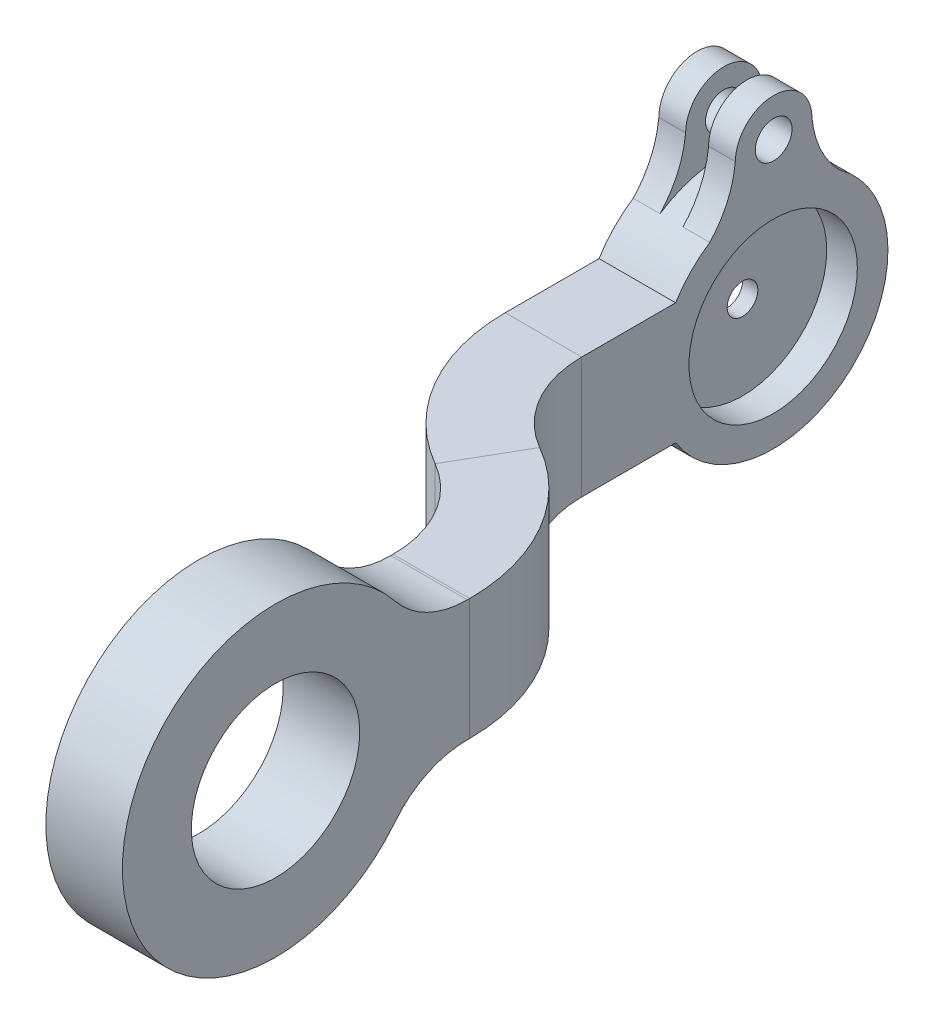
SolidWorks part; units mm, degrees
material "Resina de melamina"
ref_plane "Alzado" through (0, 0, 0) normal (0, 0, 1) x (1, 0, 0)
ref_plane "Planta" through (0, 0, 0) normal (0, 1, 0) x (1, 0, 0)
ref_plane "Vista lateral" through (0, 0, 0) normal (1, 0, 0) x (0, 0, -1)
sketch "Croquis1" plane through (0, 0, 0) normal (0, 1, 0) x (1, 0, 0)
  line L0 (0, 0) -> (0, 60) construction
  line L1 (0, 60) -> (-20, 60) construction
  line L2 (-20, 60) -> (-20, 85) construction
  line L3 (0, 15) -> (-20, 25.359) construction
  line L4 (-20, 85) -> (-20, 60)
  line L5 (0, 25.359) -> (0, 0)
  arc A0 (-20, 60) -> (-10, 42.6795) centre (0, 60) ccw
  arc A1 (0, 25.359) -> (-10, 42.6795) centre (-20, 25.359) ccw
  dimension "D4" = 20
  dimension "D1" = 60
  dimension "D2" = 25
  dimension "D3" = 20
sketch "Croquis2" plane through (0, 0, 0) normal (0, 0, 1) x (1, 0, 0)
  line L1 (5, -7.9175) -> (-5, -7.9175)
  line L2 (5, -7.9175) -> (5, 7.9175)
  line L3 (5, 7.9175) -> (-5, 7.9175)
  line L4 (-5, -7.9175) -> (-5, 7.9175)
  line L5 (5, -7.9175) -> (-5, 7.9175) construction
  line L6 (5, 7.9175) -> (-5, -7.9175) construction
  point P0 (0, 0)
  dimension "D1" = 10
sweep "Barrer1" add profiles "Croquis2" path "Croquis1"
sketch "Croquis4" plane through (-15, 0, 0) normal (1, 0, 0) x (0, 0, -1)
  line L1 (85, -7.9175) -> (85, 7.9175) construction
  circle A0 centre (85, 0) radius 15
  dimension "D2" = 30
extrude "Saliente-Extruir1" add sketch "Croquis4" against normal blind 10
sketch "Croquis5" plane through (5, 0, 0) normal (1, 0, 0) x (0, 0, -1)
  circle A0 centre (0, 0) radius 20
  dimension "D1" = 40
extrude "Saliente-Extruir2" add sketch "Croquis5" against normal blind 10
sketch "Croquis6" plane through (-15, 0, 0) normal (1, 0, 0) x (0, 0, -1)
  line L0 (60, 0) -> (85, 0) construction
  circle A0 centre (85, 0) radius 2
  dimension "D1" = 4
sketch "Croquis7" plane through (5, 0, 0) normal (1, 0, 0) x (0, 0, -1)
  circle A0 centre (0, 0) radius 11
  dimension "D1" = 22
ref_plane "Plano1" through (-15, 0, 0) normal (1, 0, 0) x (0, 0, -1)
sketch "Croquis12" plane through (-15, 0, 0) normal (1, 0, 0) x (0, 0, -1)
  line L0 (85.0685, -0.0274) -> (85.0685, 24.9726) construction
  line L1 (85.0685, 24.9726) -> (85.0685, 19.9726) construction
  line L2 (85.0685, 24.9726) -> (85.0685, 14.9726) construction
  arc A0 (90.0685, 19.9726) -> (80.0685, 19.9726) centre (85.0685, 19.9726) ccw
  arc A1 (94.2885, 11.6439) -> (75.8485, 11.6439) centre (85.0685, -0.0274) ccw
  spline S0 degree 2 poles (80.0685, 19.9726) (79.5667, 15.0283) (75.8485, 11.6439) knots 0 0 0 1 1 1
  spline S1 degree 2 poles (90.0685, 19.9726) (90.5703, 15.0283) (94.2885, 11.6439) knots 0 0 0 1 1 1
  dimension "D1" = 25
  dimension "D2" = 5
extrude "Saliente-Extruir5" add sketch "Croquis12" against normal blind 3.5
ref_plane "Plano2" through (-20, 0, 0) normal (1, 0, 0) x (0, 0, -1)
mirror "Simetría1" about plane through (-20, 0, 0) normal (1, 0, 0) of "Saliente-Extruir5"
sketch "Croquis13" plane through (-15, 0, 0) normal (1, 0, 0) x (0, 0, -1)
  circle A0 centre (85.0685, 19.9726) radius 2.4
  dimension "D1" = 4.8
extrude "Cortar-Extruir1" cut sketch "Croquis13" against normal blind 10
extrude "Cortar-Extruir3" cut sketch "Croquis7" against normal blind 10
fillet "Redondeo2" radius 12 1 edges at (0, 7.9175, -18.3661)
fillet "Redondeo3" radius 12 1 edges at (0, -7.9175, -18.3661)
sketch "Croquis14" plane through (-25, 0, 0) normal (-1, 0, 0) x (0, 0, 1)
  circle A0 centre (-85, 0) radius 11
  dimension "D1" = 22
extrude "Cortar-Extruir4" cut sketch "Croquis14" against normal blind 4
extrude "Cortar-Extruir5" cut sketch "Croquis6" against normal blind 6 contours A0
sketch "Croquis15" plane through (-15, 0, 0) normal (1, 0, 0) x (0, 0, -1)
  circle A0 centre (85, 0) radius 11
  dimension "D1" = 22
extrude "Cortar-Extruir6" cut sketch "Croquis15" against normal blind 4
